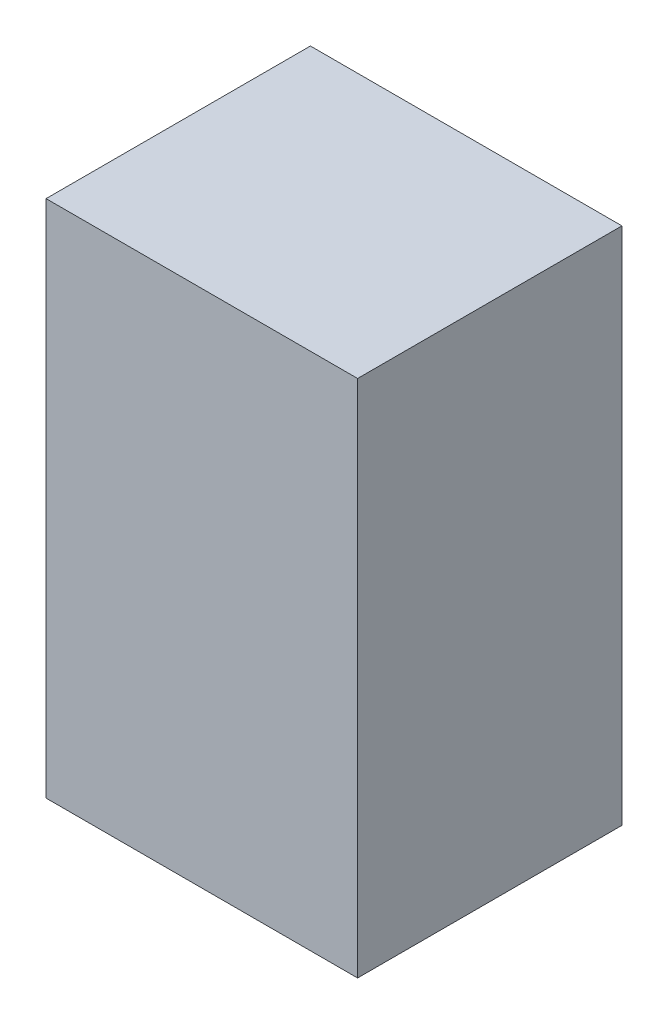
SolidWorks part; units mm, degrees
ref_plane "Front Plane" through (0, 0, 0) normal (0, 0, 1) x (1, 0, 0)
ref_plane "Top Plane" through (0, 0, 0) normal (0, 1, 0) x (1, 0, 0)
ref_plane "Right Plane" through (0, 0, 0) normal (1, 0, 0) x (0, 0, -1)
sketch "Sketch1" plane through (0, 0, 0) normal (0, 1, 0) x (1, 0, 0)
  line L1 (0, 0) -> (838.2, 0)
  line L2 (0, 0) -> (0, 711.2)
  line L3 (0, 711.2) -> (838.2, 711.2)
  line L4 (838.2, 0) -> (838.2, 711.2)
  dimension "D1" = 838.2
  dimension "D2" = 711.2
extrude "Boss-Extrude1" add sketch "Sketch1" along normal blind 1397
sketch "Sketch2" plane through (0, 0, -711.2) normal (0, 0, -1) x (-1, 0, 0)
  line L0 (-838.2, 1397) -> (-838.2, 0) construction
  line L2 (-805.0188, 2198.0525) -> (-918.4948, 1885.2996)
  line L3 (-838.2, 0) -> (0, 0)
  line L4 (-838.2, 0) -> (-838.2, 177.8)
  line L5 (-838.2, 177.8) -> (0, 177.8)
  line L6 (0, 0) -> (0, 177.8)
  line L7 (0, 1397) -> (0, 0) construction
  line L8 (-838.2, 1397) -> (0, 1397) construction
  line L9 (0, 177.8) -> (-50.8, 177.8)
  line L10 (0, 177.8) -> (0, 1397)
  line L11 (0, 1397) -> (-50.8, 1397)
  line L12 (-50.8, 177.8) -> (-50.8, 1397)
  line L13 (-50.8, 1092.2) -> (-777.6551, 2006.9897)
  line L14 (-838.2, 0) -> (0, 0) construction
  line L16 (-542.3725, 2102.7567) -> (-655.8486, 1790.0037)
  line L17 (-918.4948, 1885.2996) -> (-655.8486, 1790.0037)
  point P19 (0, 0)
  point P20 (0, 0)
  point P21 (0, 0)
  point P22 (-833.0983, 285.43)
  point P23 (0, 0)
  point P24 (0, 0)
  point P25 (0, 0)
  point P26 (-718.0338, 133.0558)
  point P27 (-1077.3992, 534.2998)
  point P28 (-1197.3674, 1327.4817)
  point P29 (-849.2754, 1948.0103)
  point P30 (-746.094, 2031.202)
  point P31 (-943.39, 1846.1506)
  point P32 (-777.6551, 2006.9897)
  dimension "D1" = 177.8
  dimension "D2" = 1168.4
  dimension "D3" = 50.8
  dimension "D4" = 304.8
  dimension "D5" = 2006.9897
  dimension "D6" = 58.412
  dimension "D7" = 90
  dimension "D8" = 243.7888
  dimension "D9" = 2.459
  dimension "D10" = 279.4
  dimension "D11" = 90.8893
